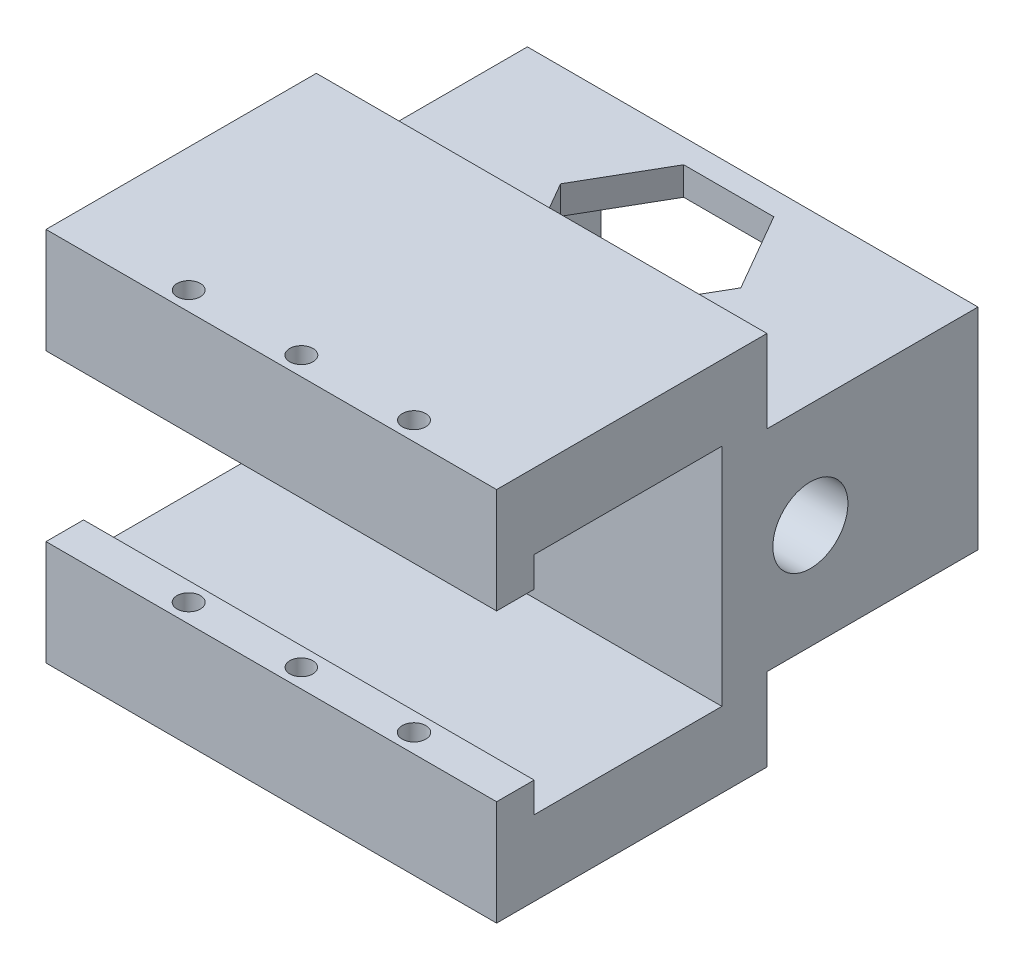
SolidWorks part; units mm, degrees
ref_plane "前视基准面" through (0, 0, 0) normal (0, 0, 1) x (1, 0, 0)
ref_plane "上视基准面" through (0, 0, 0) normal (0, 1, 0) x (1, 0, 0)
ref_plane "右视基准面" through (0, 0, 0) normal (1, 0, 0) x (0, 0, -1)
sketch "草图1" plane through (0, 0, 0) normal (0, 0, 1) x (1, 0, 0)
  line L1 (30, -25) -> (-30, -25)
  line L2 (30, -25) -> (30, 25)
  line L3 (30, 25) -> (-30, 25)
  line L4 (-30, -25) -> (-30, 25)
  line L5 (30, -25) -> (-30, 25) construction
  line L6 (30, 25) -> (-30, -25) construction
  point P0 (0, 0)
  dimension "D1" = 50
  dimension "D2" = 60
extrude "凸台-拉伸1" add sketch "草图1" along normal blind 6
sketch "草图2" plane through (0, 0, 6) normal (0, 0, 1) x (1, 0, 0)
  line L0 (30, -25) -> (30, 25) construction
  line L1 (-30, 25) -> (30, 25)
  line L2 (-30, 25) -> (-30, 15)
  line L3 (-30, 15) -> (30, 15)
  line L4 (30, 25) -> (30, 15)
  line L6 (-30, -25) -> (30, -25)
  line L7 (-30, -25) -> (-30, -15)
  line L8 (-30, -15) -> (30, -15)
  line L9 (30, -25) -> (30, -15)
  dimension "D1" = 10
  dimension "D2" = 10
extrude "凸台-拉伸3" add sketch "草图2" along normal blind 30
sketch "草图3" plane through (0, -15, 0) normal (0, 1, 0) x (1, 0, 0)
  line L0 (30, -36) -> (30, -6) construction
  line L1 (-30, -36) -> (30, -36)
  line L2 (-30, -36) -> (-30, -31)
  line L3 (-30, -31) -> (30, -31)
  line L4 (30, -36) -> (30, -31)
  dimension "D1" = 5
extrude "凸台-拉伸4" add sketch "草图3" along normal blind 4
sketch "草图4" plane through (0, 15, 0) normal (0, -1, 0) x (1, 0, 0)
  line L0 (30, 36) -> (30, 6) construction
  line L1 (-30, 36) -> (30, 36)
  line L2 (-30, 36) -> (-30, 31)
  line L3 (-30, 31) -> (30, 31)
  line L4 (30, 36) -> (30, 31)
  dimension "D1" = 5
extrude "凸台-拉伸5" add sketch "草图4" along normal blind 4
sketch "草图6" plane through (0, -11, 0) normal (0, 1, 0) x (1, 0, 0)
  circle A0 centre (-13.5, -33.5) radius 1.5557
  circle A1 centre (1.5, -33.5) radius 1.5331
  circle A2 centre (16.5, -33.5) radius 1.574
sketch "草图7" plane through (0, 11, 0) normal (0, -1, 0) x (1, 0, 0)
  circle A0 centre (16.5, 33.5) radius 1.55
  circle A1 centre (1.5, 33.5) radius 1.55
  circle A2 centre (-13.5, 33.5) radius 1.55
extrude "切除-拉伸1" cut sketch "草图6" against normal through all
extrude "切除-拉伸2" cut sketch "草图7" against normal through all
sketch "草图9" plane through (0, 0, 0) normal (0, 0, -1) x (-1, 0, 0)
  line L1 (20.2, -10.25) -> (-20.2, -10.25)
  line L2 (20.2, -10.25) -> (20.2, 10.25)
  line L3 (20.2, 10.25) -> (-20.2, 10.25)
  line L4 (-20.2, -10.25) -> (-20.2, 10.25)
  line L5 (20.2, -10.25) -> (-20.2, 10.25) construction
  line L6 (20.2, 10.25) -> (-20.2, -10.25) construction
  line L7 (30, -14) -> (-30, -14)
  line L8 (30, -14) -> (30, 14)
  line L9 (30, 14) -> (-30, 14)
  line L10 (-30, -14) -> (-30, 14)
  line L11 (30, -14) -> (-30, 14) construction
  line L12 (30, 14) -> (-30, -14) construction
  point P0 (0, 0)
  point P5 (0, 0)
  dimension "D1" = 20.5
  dimension "D2" = 40.4
  dimension "D3" = 28
  dimension "D4" = 60
extrude "凸台-拉伸6" add sketch "草图9" along normal blind 28.1
sketch "草图11" plane through (30, 0, 0) normal (1, 0, 0) x (0, 0, -1)
  circle A0 centre (5.7817, 0) radius 5
  dimension "D1" = 10
extrude "切除-拉伸3" cut sketch "草图11" against normal blind 10
sketch "草图12" plane through (0, 0, -28.1) normal (0, 0, -1) x (-1, 0, 0)
  circle A0 centre (24.8, -5) radius 2.25
  circle A1 centre (24.8, 5) radius 2.25
  circle A2 centre (-24.8, -5) radius 2.25
  circle A3 centre (-24.8, 5) radius 2.25
extrude "切除-拉伸4" cut sketch "草图12" against normal blind 16
sketch "草图13" plane through (0, 14, 0) normal (0, 1, 0) x (1, 0, 0)
  line L1 (-12, 14.5188) -> (-6, 4.1265)
  line L2 (-6, 4.1265) -> (6, 4.1265)
  line L3 (6, 4.1265) -> (12, 14.5188)
  line L4 (12, 14.5188) -> (6, 24.9111)
  line L5 (6, 24.9111) -> (-6, 24.9111)
  line L6 (-6, 24.9111) -> (-12, 14.5188)
  circle A0 centre (0, 14.5188) radius 10.3923 construction
  dimension "D1" = 12
extrude "切除-拉伸5" cut sketch "草图13" against normal through all
